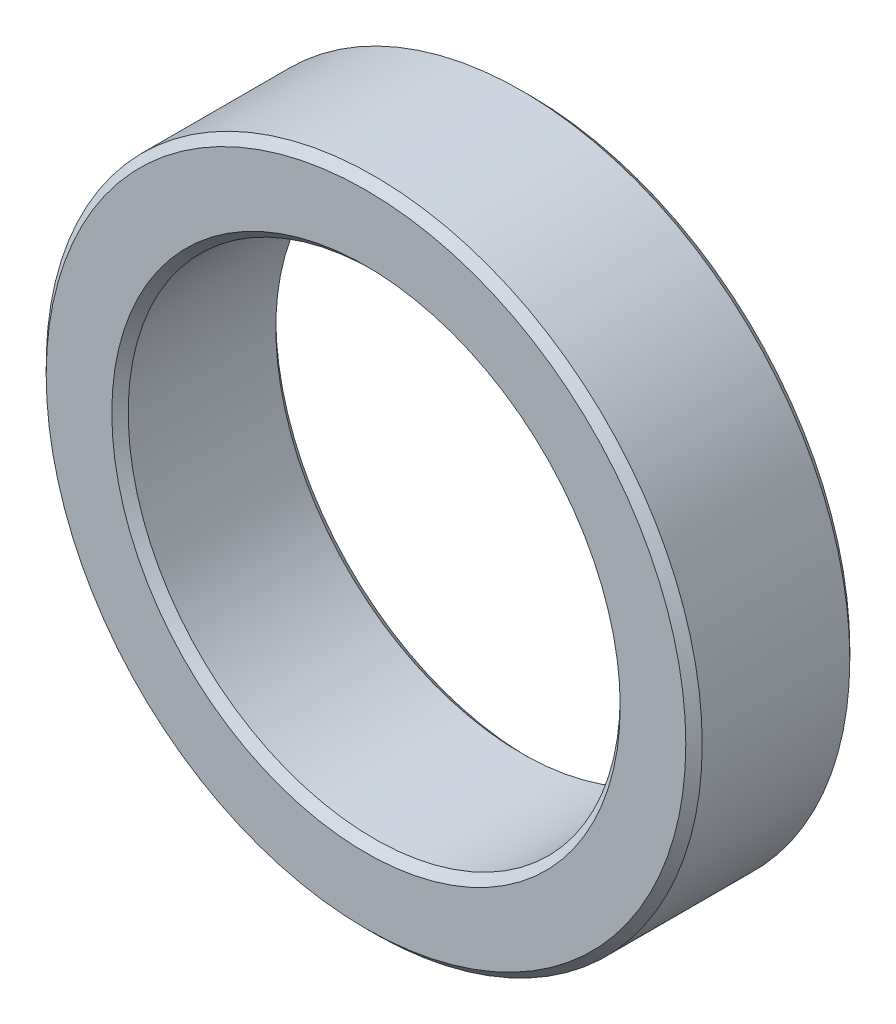
SolidWorks part; units mm, degrees
material "POM copolymère d'acétal"
ref_plane "Face" through (0, 0, 0) normal (0, 0, 1) x (1, 0, 0)
ref_plane "Dessus" through (0, 0, 0) normal (0, 1, 0) x (1, 0, 0)
ref_plane "Droite" through (0, 0, 0) normal (1, 0, 0) x (0, 0, -1)
sketch "Esquisse1" plane through (0, 0, 0) normal (0, 0, 1) x (1, 0, 0)
  circle A0 centre (0, 0) radius 6
  circle A1 centre (0, 0) radius 8
  dimension "D1" = 12
  dimension "D2" = 16
extrude "Boss.-Extru.1" add sketch "Esquisse1" along normal blind 4
chamfer "Chanfrein1" distance 0.2 angle 45 4 edges at (6, 0, 0) (6, 0, 4) (8, 0, 0) (8, 0, 4)
